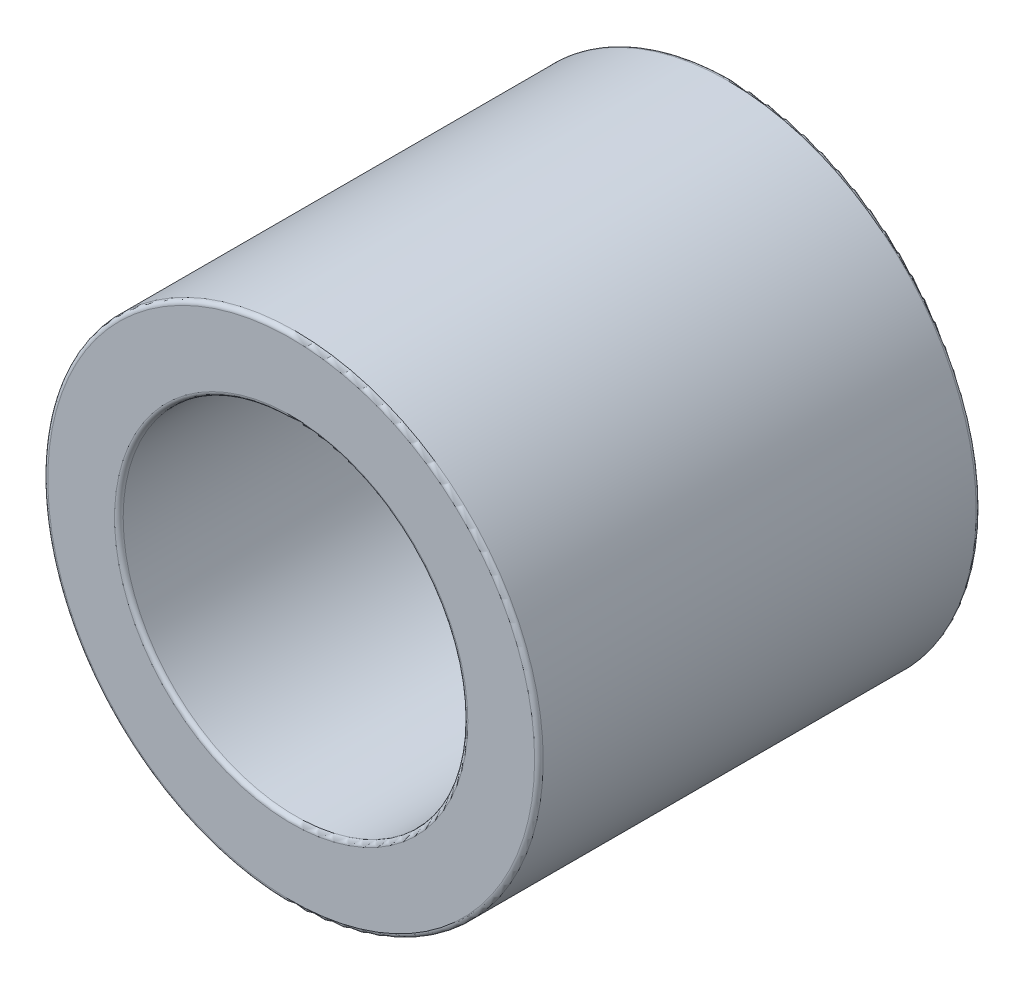
SolidWorks part; units mm, degrees
material "Plain Carbon Steel"
ref_plane "Front Plane" through (0, 0, 0) normal (0, 0, 1) x (1, 0, 0)
ref_plane "Top Plane" through (0, 0, 0) normal (0, 1, 0) x (1, 0, 0)
ref_plane "Right Plane" through (0, 0, 0) normal (1, 0, 0) x (0, 0, -1)
sketch "Sketch1" plane through (0, 0, 0) normal (0, 0, 1) x (1, 0, 0)
  circle A0 centre (0, 0) radius 5.75
  circle A1 centre (0, 0) radius 4
  dimension "D1" = 1.75
  dimension "D2" = 8
extrude "Boss-Extrude1" add sketch "Sketch1" along normal mid plane 10.25
fillet "Fillet1" radius 0.1 4 edges at (4, 0, 5.125) (4, 0, -5.125) (5.75, 0, -5.125) (5.75, 0, 5.125)
